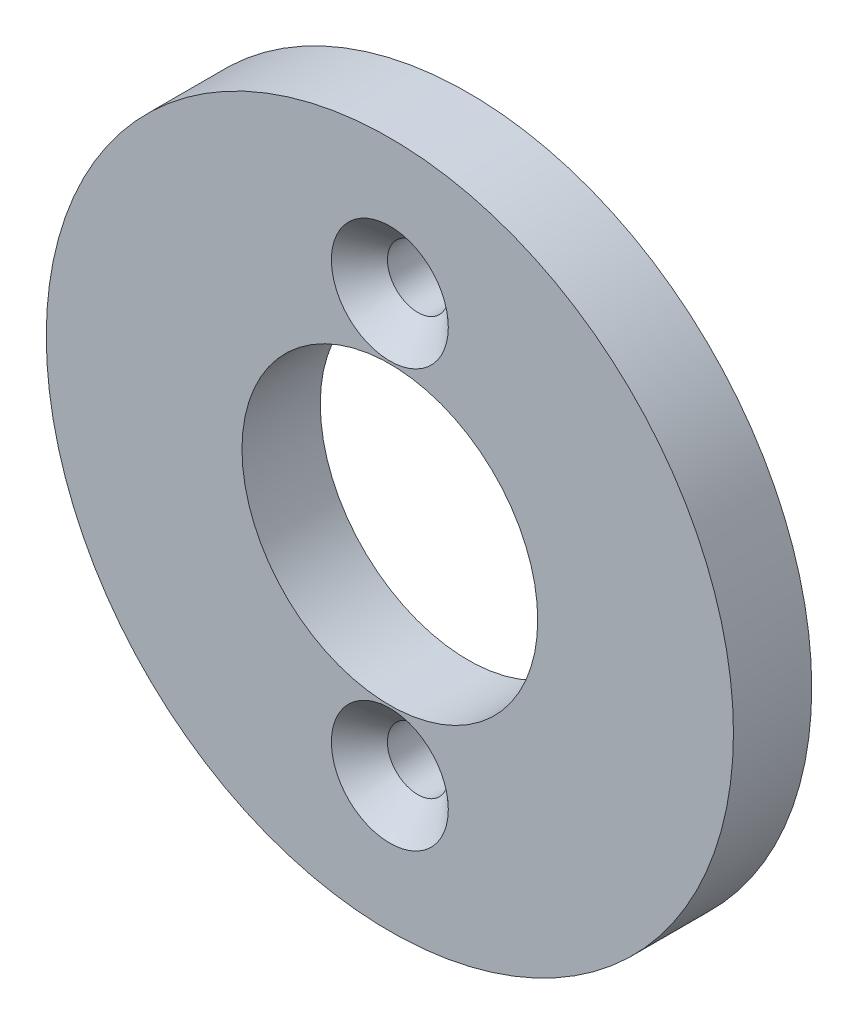
SolidWorks part; units mm, degrees
ref_plane "正面" through (0, 0, 0) normal (0, 0, 1) x (1, 0, 0)
ref_plane "平面" through (0, 0, 0) normal (0, 1, 0) x (1, 0, 0)
ref_plane "右側面" through (0, 0, 0) normal (1, 0, 0) x (0, 0, -1)
sketch "ｽｹｯﾁ1" plane through (0, 0, 0) normal (0, 0, 1) x (1, 0, 0)
  circle A0 centre (0, 0) radius 39.5
extrude "ﾎﾞｽ - 押し出し1" add sketch "ｽｹｯﾁ1" along normal blind 9
sketch "ｽｹｯﾁ2" plane through (0, 0, 0) normal (0, 0, 1) x (1, 0, 0)
  circle A0 centre (0, 0) radius 17
  circle A1 centre (0, 24) radius 3.5
  circle A2 centre (0, -24) radius 3.5
extrude "ｶｯﾄ - 押し出し1" cut sketch "ｽｹｯﾁ2" against normal through all and the other way through all
sketch "ｽｹｯﾁ3" plane through (0, 0, 9) normal (0, 0, 1) x (1, 0, 0)
  circle A0 centre (0, 24) radius 6.72
  circle A1 centre (0, -24) radius 6.72
extrude "ｶｯﾄ - 押し出し2" cut sketch "ｽｹｯﾁ3" against normal blind 3.22 draft 45
